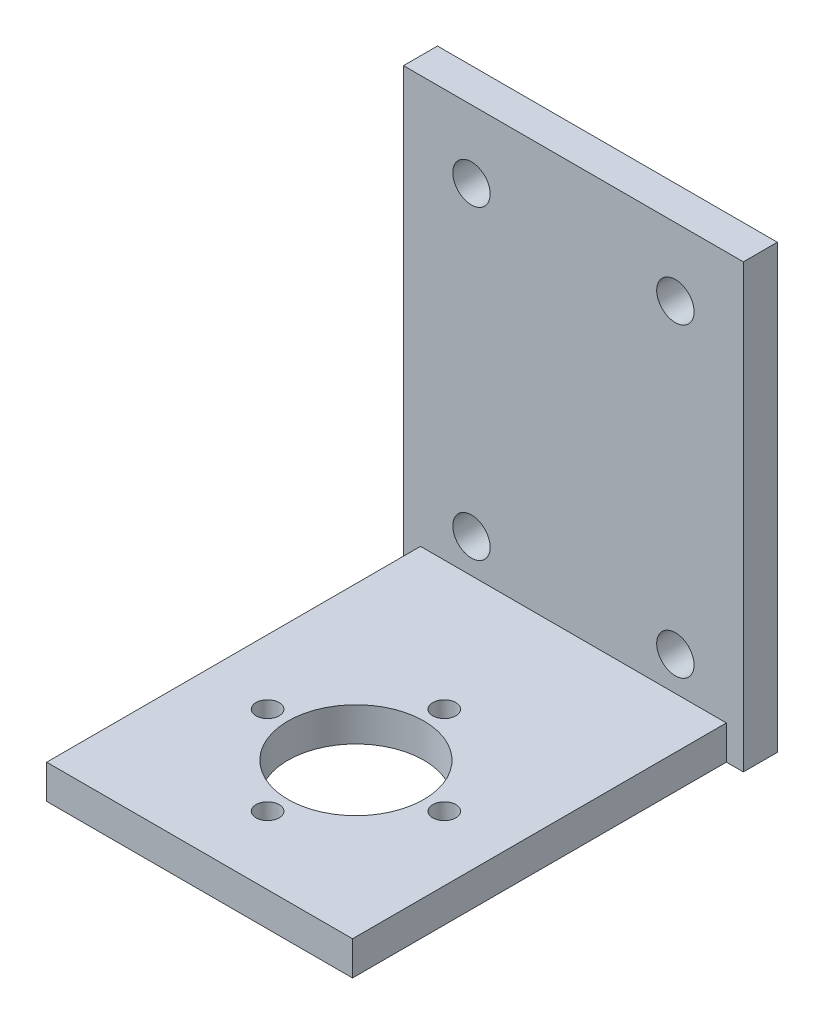
SolidWorks part; units mm, degrees
ref_plane "Front Plane" through (0, 0, 0) normal (1, 0, 0) x (0, 1, 0)
ref_plane "Top Plane" through (0, 0, 0) normal (0, 0, 1) x (0, 1, 0)
ref_plane "Right Plane" through (0, 0, 0) normal (0, 1, 0) x (-1, 0, 0)
sketch "Sketch1" plane through (0, 0, 0) normal (0, 0, 1) x (0, 1, 0)
  line L1 (-32.5, -25) -> (32.5, -25)
  line L2 (-32.5, -25) -> (-32.5, 25)
  line L3 (-32.5, 25) -> (32.5, 25)
  line L4 (32.5, -25) -> (32.5, 25)
  line L5 (-32.5, -25) -> (32.5, 25) construction
  line L6 (-32.5, 25) -> (32.5, -25) construction
  point P0 (0, 0)
  dimension "D1" = 65
  dimension "D2" = 50
extrude "Boss-Extrude1" add sketch "Sketch1" along normal blind 5
sketch "Sketch2" plane through (0, 0, 5) normal (0, 0, 1) x (1, 0, 0)
  line L0 (0, -32.5) -> (-22.5, -32.5)
  line L1 (0, -32.5) -> (0, 32.217) construction
  line L2 (-25, -32.5) -> (25, -32.5) construction
  line L3 (-22.5, -32.5) -> (-22.5, -27.5)
  line L4 (-22.5, -27.5) -> (22.5, -27.5)
  line L5 (22.5, -27.5) -> (22.5, -32.5)
  line L6 (22.5, -32.5) -> (0, -32.5)
  dimension "D1" = 22.5
  dimension "D2" = 22.5
  dimension "D3" = 5
extrude "Boss-Extrude2" add sketch "Sketch2" along normal blind 55
sketch "Sketch3" plane through (0, -32.5, 0) normal (0, -1, 0) x (1, 0, 0)
  line L0 (22.5, 5) -> (25, 5) construction
  circle A0 centre (0, 37) radius 10
  dimension "D1" = 20
  dimension "D2" = 32
extrude "Cut-Extrude1" cut sketch "Sketch3" against normal through all
sketch "Sketch4" plane through (0, -32.5, 0) normal (0, -1, 0) x (1, 0, 0)
  circle A0 centre (0, 37) radius 13 construction
  dimension "D1" = 26
sketch "Sketch5" plane through (0, -32.5, 0) normal (0, -1, 0) x (1, 0, 0)
  circle A0 centre (0, 50) radius 1.7
  circle A1 centre (0, 37) radius 13 construction
  circle A2 centre (13, 37) radius 1.7
  circle A3 centre (0, 24) radius 1.7
  circle A4 centre (-13, 37) radius 1.7
  dimension "D1" = 3.4
  dimension "D2" = 3.4
  dimension "D3" = 3.4
  dimension "D4" = 3.4
extrude "Cut-Extrude2" cut sketch "Sketch5" against normal through all
sketch "Sketch6" plane through (0, 0, 5) normal (0, 0, 1) x (1, 0, 0)
  line L0 (25, 32.5) -> (-25, 32.5) construction
  line L1 (-25, 32.5) -> (-25, -32.5) construction
  line L2 (25, -32.5) -> (25, 32.5) construction
  line L3 (22.5, -27.5) -> (-22.5, -27.5) construction
  circle A0 centre (-15, 22.5) radius 2.75
  circle A1 centre (15, 22.5) radius 2.75
  circle A2 centre (-15, -22.5) radius 2.75
  circle A3 centre (15, -22.5) radius 2.75
  point P12 (-17.3702, 31.8258)
  dimension "D1" = 5.5
  dimension "D2" = 5.5
  dimension "D3" = 5.5
  dimension "D4" = 5.5
  dimension "D5" = 10
  dimension "D6" = 10
  dimension "D7" = 10
  dimension "D8" = 10
  dimension "D9" = 10
  dimension "D10" = 5
  dimension "D11" = 5
  dimension "D12" = 10
extrude "Cut-Extrude3" cut sketch "Sketch6" against normal through all
